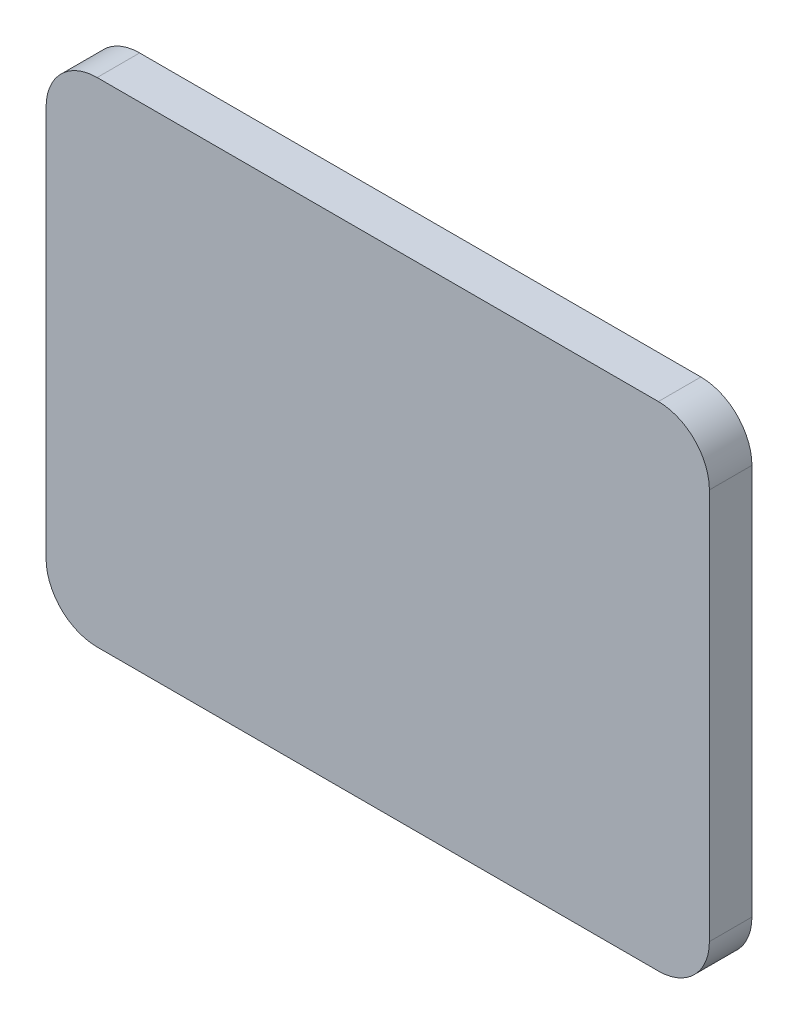
SolidWorks part; units mm, degrees
ref_plane "Front Plane" through (0, 0, 0) normal (0, 0, 1) x (1, 0, 0)
ref_plane "Top Plane" through (0, 0, 0) normal (0, 1, 0) x (1, 0, 0)
ref_plane "Right Plane" through (0, 0, 0) normal (1, 0, 0) x (0, 0, -1)
sketch "Sketch2" plane through (0, 0, 0) normal (0, 0, 1) x (1, 0, 0)
  line L1 (-49.53, 36.83) -> (49.53, 36.83)
  line L2 (-49.53, 36.83) -> (-49.53, -36.83)
  line L3 (-49.53, -36.83) -> (49.53, -36.83)
  line L4 (49.53, 36.83) -> (49.53, -36.83)
  line L5 (-49.53, 36.83) -> (49.53, -36.83) construction
  line L6 (-49.53, -36.83) -> (49.53, 36.83) construction
  point P0 (0, 0)
  dimension "D1" = 99.06
  dimension "D2" = 73.66
extrude "Boss-Extrude1" add sketch "Sketch2" along normal blind 6.35
fillet "Fillet1" radius 7.62 4 edges at (-49.53, -36.83, 3.175) (49.53, -36.83, 3.175) (49.53, 36.83, 3.175) (-49.53, 36.83, 3.175)
